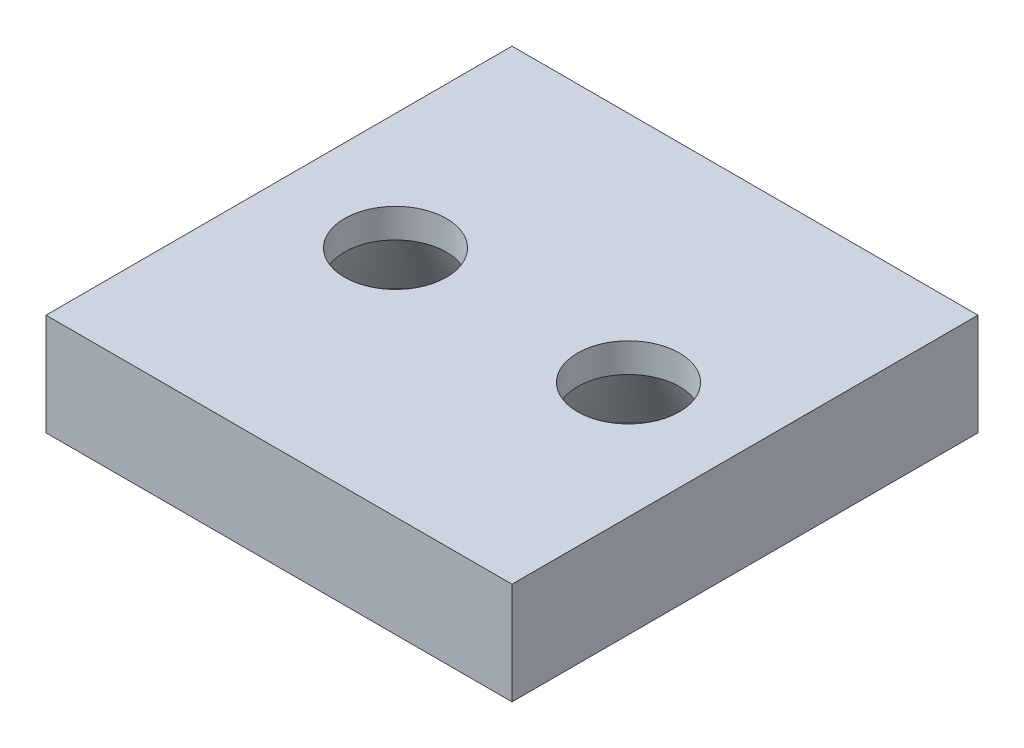
SolidWorks part; units mm, degrees
material "AISI 1020"
ref_plane "Front Plane" through (0, 0, 0) normal (0, 0, 1) x (1, 0, 0)
ref_plane "Top Plane" through (0, 0, 0) normal (0, 1, 0) x (1, 0, 0)
ref_plane "Right Plane" through (0, 0, 0) normal (1, 0, 0) x (0, 0, -1)
sketch "Sketch1" plane through (0, 0, 0) normal (0, 1, 0) x (1, 0, 0)
  line L1 (-16, 16) -> (16, 16)
  line L2 (-16, 16) -> (-16, -16)
  line L3 (-16, -16) -> (16, -16)
  line L4 (16, 16) -> (16, -16)
  line L5 (-16, 16) -> (16, -16) construction
  line L6 (-16, -16) -> (16, 16) construction
  point P0 (0, 0)
  dimension "D1" = 32
  dimension "D2" = 32
extrude "Boss-Extrude1" add sketch "Sketch1" along normal blind 7
hole_wizard "CSK for M2 Flat Head Machine Screw1" positions "Sketch2" profile "Sketch3" countersink size "M2" standard "ANSI Metric"
sketch "Sketch2" plane through (0, 0, 0) normal (0, -1, 0) x (-1, 0, 0)
  line L0 (16, 16) -> (16, -16) construction
  point P0 (8, 0)
  dimension "D1" = 8
sketch "Sketch3" plane through (-8, 0, 0) normal (1, 0, 0) x (0, 0, -1)
  line L0 (0, 0) -> (0, 18.0207)
  line L1 (0, 18.0207) -> (3.5, 16)
  line L2 (3.5, 16) -> (3.5, 4.9998)
  line L3 (3.5, 4.9998) -> (6.5, 0)
  line L5 (6.5, 0) -> (0, 0)
  line L6 (-3.5, 4.9998) -> (-6.5, 0) construction
  line L10 (0, 18.0207) -> (-3.5, 16) construction
  line L11 (0, -6.35) -> (0, 107.95) construction
  dimension "Hole Dia." = 7
  dimension "Hole Depth" = 16
  dimension "Near C'Sink Dia." = 13
  dimension "Near C'Sink Angle" = 61.93
  dimension "Drill Angle" = 120
pattern_linear "LPattern1" count 2 spacing 16 along (1, 0, 0) of "CSK for M2 Flat Head Machine Screw1"
